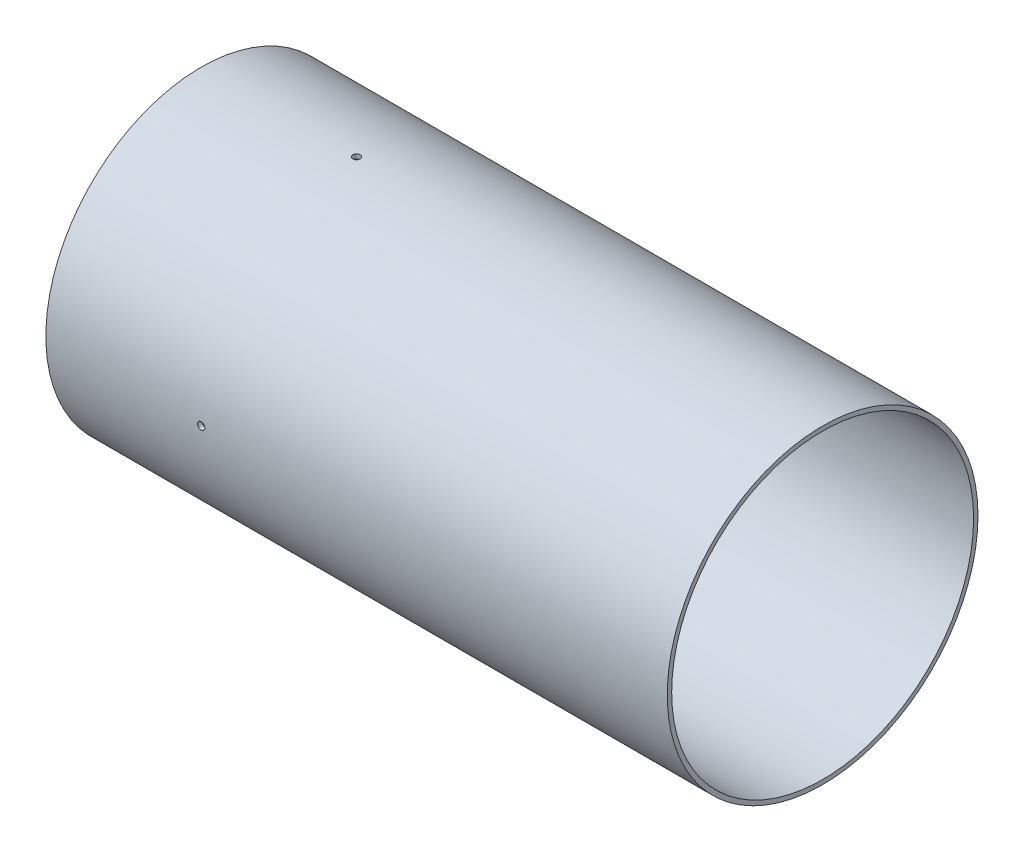
SolidWorks part; units mm, degrees
material "E-Glass Fiber"
ref_plane "Front Plane" through (0, 0, 0) normal (0, 0, 1) x (1, 0, 0)
ref_plane "Top Plane" through (0, 0, 0) normal (0, 1, 0) x (1, 0, 0)
ref_plane "Right Plane" through (0, 0, 0) normal (1, 0, 0) x (0, 0, -1)
sketch "Sketch1" plane through (0, 0, 0) normal (1, 0, 0) x (0, 0, -1)
  circle A0 centre (0, 0) radius 74.041
  circle A1 centre (0, 0) radius 76.2
  dimension "D1" = 152.4
  dimension "D2" = 2.159
extrude "Boss-Extrude1" add sketch "Sketch1" along normal blind 304.8
sketch "Sketch2" plane through (0, 0, 0) normal (0, 0, 1) x (1, 0, 0)
  line L0 (0, 76.2) -> (0, -76.2) construction
  circle A0 centre (76.2, 0) radius 1.7859
  point P4 (0, 0)
  dimension "D2" = 3.5719
  dimension "D1" = 76.2
extrude "Cut-Extrude1" cut sketch "Sketch2" against normal up to surface (76.2 mm away) up to face at (304.8, 0, -76.2)
pattern_circular "CirPattern1" count 4 over 360 about axis through (0, 0, 0) along (1, 0, 0) of "Cut-Extrude1"
